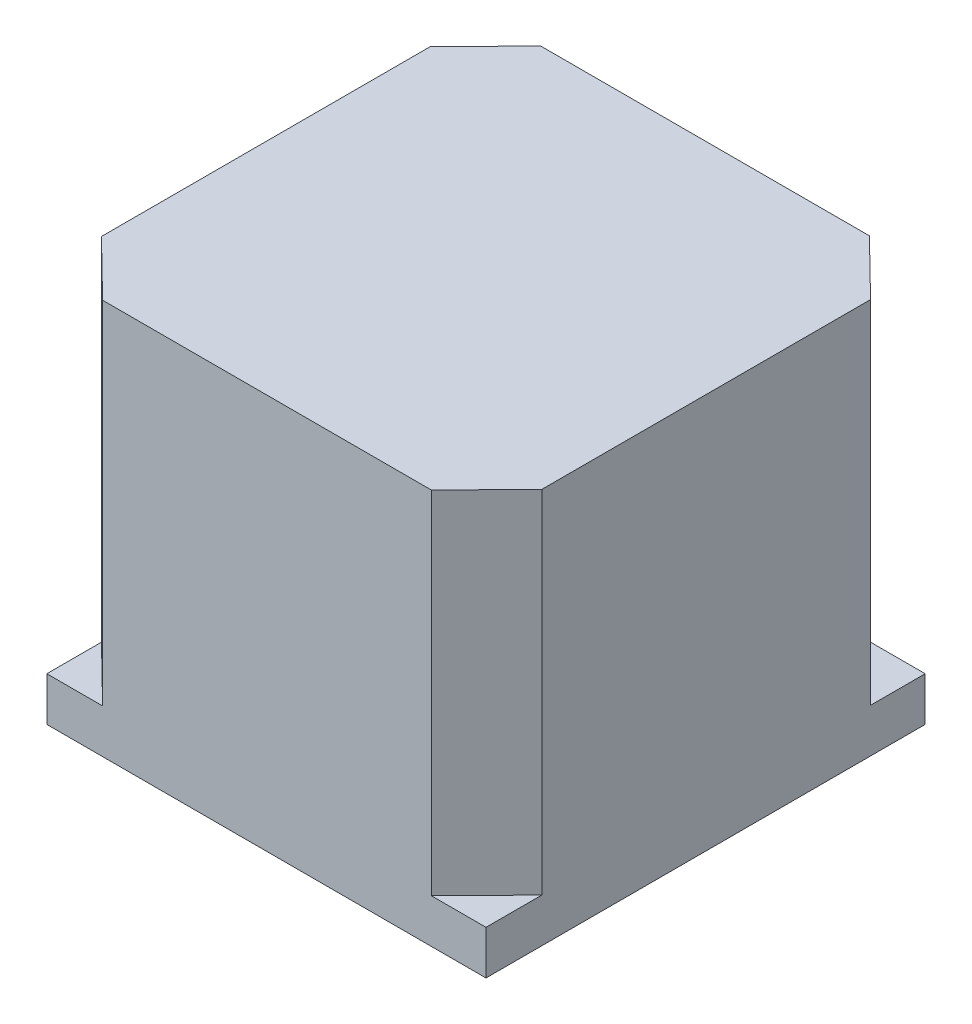
SolidWorks part; units mm, degrees
ref_plane "Front Plane" through (0, 0, 0) normal (0, 0, 1) x (1, 0, 0)
ref_plane "Top Plane" through (0, 0, 0) normal (0, 1, 0) x (1, 0, 0)
ref_plane "Right Plane" through (0, 0, 0) normal (1, 0, 0) x (0, 0, -1)
sketch "Sketch1" plane through (0, 0, 0) normal (0, 1, 0) x (1, 0, 0)
  line L1 (-50, -50) -> (50, -50)
  line L2 (-50, -50) -> (-50, 50)
  line L3 (-50, 50) -> (50, 50)
  line L4 (50, -50) -> (50, 50)
  line L5 (-50, -50) -> (50, 50) construction
  line L6 (-50, 50) -> (50, -50) construction
  point P0 (0, 0)
  dimension "D1" = 100
  dimension "D2" = 100
extrude "Boss-Extrude1" add sketch "Sketch1" along normal blind 90
sketch "Sketch2" plane through (0, 90, 0) normal (0, 1, 0) x (1, 0, 0)
  line L0 (-50, 37.3) -> (-37.5567, 50)
  line L1 (-50, 50) -> (-50, -50) construction
  line L2 (50, 50) -> (-50, 50) construction
  line L3 (-37.5567, 50) -> (37.3, 50)
  line L4 (37.3, 50) -> (50, 37.5567)
  line L5 (50, -50) -> (50, 50) construction
  line L6 (50, 37.5567) -> (50, -37.3)
  line L7 (50, -37.3) -> (37.5567, -50)
  line L8 (-50, -50) -> (50, -50) construction
  line L9 (37.5567, -50) -> (-37.3, -50)
  line L10 (-37.3, -50) -> (-50, -37.5567)
  line L11 (-50, -37.5567) -> (-50, 37.3)
  line L12 (-50, -50) -> (50, -50)
  line L13 (50, -50) -> (50, 50)
  line L14 (50, 50) -> (-50, 50)
  line L15 (-50, 50) -> (-50, -50)
  line M9 (50, -50) -> (50, 50)
  line M10 (50, 50) -> (-50, 50)
  line M11 (-50, 50) -> (-50, -50)
  line M12 (-50, -50) -> (50, -50)
extrude "Cut-Extrude1" cut sketch "Sketch2" against normal blind 80 contours L0 M11 M10 | L10 M12 M11 | L7 M9 M12 | L4 M10 M9
